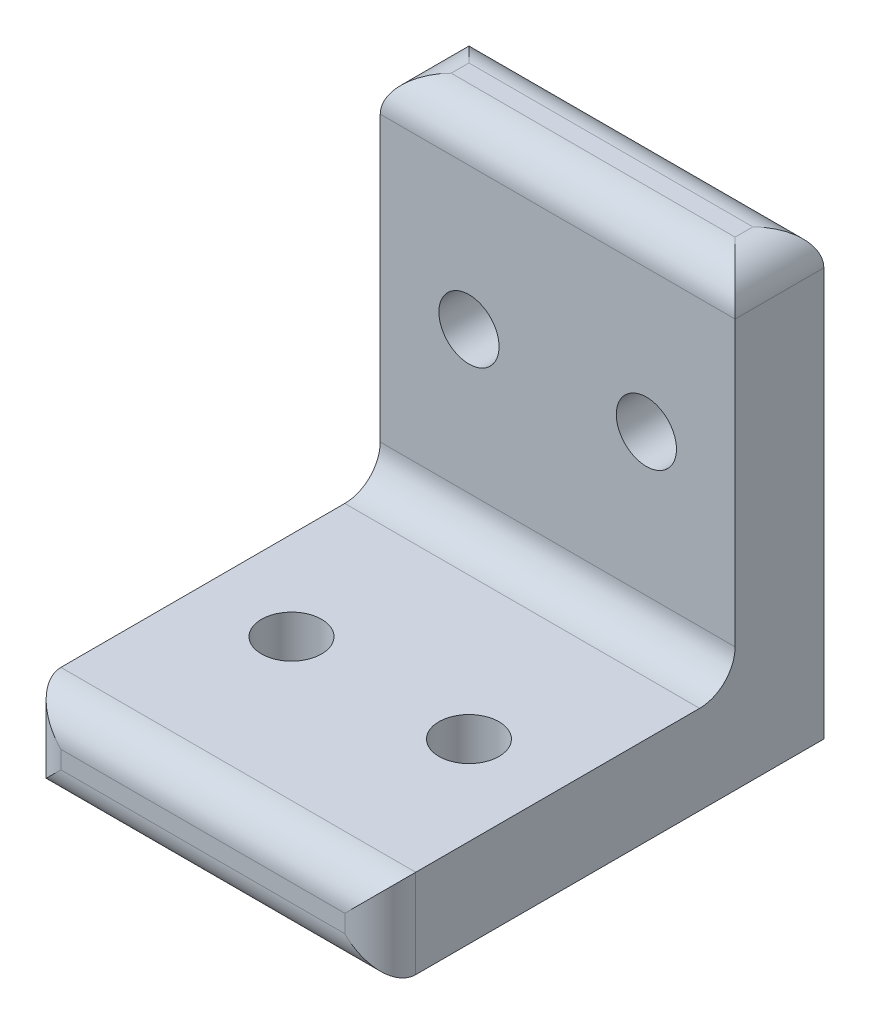
SolidWorks part; units mm, degrees
ref_plane "Front Plane" through (0, 0, 0) normal (0, 0, 1) x (1, 0, 0)
ref_plane "Top Plane" through (0, 0, 0) normal (0, 1, 0) x (1, 0, 0)
ref_plane "Right Plane" through (0, 0, 0) normal (1, 0, 0) x (0, 0, -1)
sketch "Sketch1" plane through (0, 0, 0) normal (0, 1, 0) x (1, 0, 0)
  line L1 (-12.7, -12.7) -> (12.7, -12.7)
  line L2 (-12.7, -12.7) -> (-12.7, 12.7)
  line L3 (-12.7, 12.7) -> (12.7, 12.7)
  line L4 (12.7, -12.7) -> (12.7, 12.7)
  line L5 (-12.7, -12.7) -> (12.7, 12.7) construction
  line L6 (-12.7, 12.7) -> (12.7, -12.7) construction
  point P0 (0, 0)
  dimension "D1" = 25.4
  dimension "D2" = 25.4
extrude "Boss-Extrude1" add sketch "Sketch1" along normal blind 6.35
sketch "Sketch2" plane through (0, 0, -12.7) normal (0, 0, -1) x (-1, 0, 0)
  line L1 (-12.7, 31.75) -> (12.7, 31.75)
  line L2 (-12.7, 31.75) -> (-12.7, 0)
  line L3 (-12.7, 0) -> (12.7, 0)
  line L4 (12.7, 31.75) -> (12.7, 0)
  line L5 (-12.7, 31.75) -> (12.7, 0) construction
  line L6 (-12.7, 0) -> (12.7, 31.75) construction
  point P0 (0, 15.875)
  dimension "D1" = 31.75
  dimension "D2" = 25.4
extrude "Boss-Extrude2" add sketch "Sketch2" along normal blind 6.35
fillet "Fillet1" radius 2.54 9 edges at (-12.7, 31.75, -15.875) (12.7, 31.75, -15.875) (-12.7, 3.175, 12.7) (12.7, 3.175, 12.7) (0, 31.75, -19.05) (0, 31.75, -12.7) (0, 0, 12.7) (0, 6.35, 12.7) (0, 6.35, -12.7)
sketch "Sketch3" plane through (0, 6.35, 0) normal (0, 1, 0) x (1, 0, 0)
  line L2 (-12.7, 10.16) -> (-12.7, -10.16) construction
  line L3 (12.7, -10.16) -> (12.7, 10.16) construction
  point P0 (-6.35, 0)
  point P1 (6.35, 0)
  dimension "D1" = 6.35
  dimension "D2" = 6.35
sketch "Sketch4" plane through (0, 0, -12.7) normal (0, 0, 1) x (1, 0, 0)
  line L0 (-12.7, 8.89) -> (12.7, 8.89) construction
  line L1 (-12.7, 8.89) -> (-12.7, 29.21) construction
  line L2 (12.7, 29.21) -> (12.7, 8.89) construction
  point P0 (6.35, 19.05)
  point P3 (-6.35, 19.05)
  dimension "D1" = 10.16
  dimension "D2" = 6.35
  dimension "D3" = 6.35
hole_wizard "#8 Clearance Hole1" positions "Sketch5" profile "Sketch6" hole size "#8" standard "ANSI Inch" end condition through all
sketch "Sketch5" plane through (0, 6.35, 0) normal (0, 1, 0) x (1, 0, 0)
  point P3 (-6.35, 0)
  point P6 (6.35, 0)
sketch "Sketch6" plane through (-6.35, 6.35, 0) normal (1, 0, 0) x (0, 0, 1)
  line L0 (0, 0) -> (0, 6.35)
  line L1 (0, 6.35) -> (2.1526, 6.35)
  line L2 (2.1526, 6.35) -> (2.1526, 0)
  line L5 (2.1526, 0) -> (0, 0)
  line L11 (0, -6.35) -> (0, 107.95) construction
  dimension "Thru Hole Dia." = 4.3053
  dimension "Thru Hole Depth" = 6.35
hole_wizard "#8 Clearance Hole2" positions "Sketch7" profile "Sketch8" hole size "#8" standard "ANSI Inch" end condition through all
sketch "Sketch7" plane through (0, 0, -12.7) normal (0, 0, 1) x (1, 0, 0)
  point P0 (6.35, 19.05)
  point P3 (-6.35, 19.05)
sketch "Sketch8" plane through (6.35, 19.05, -12.7) normal (1, 0, 0) x (0, -1, 0)
  line L0 (0, 0) -> (0, 6.35)
  line L1 (0, 6.35) -> (2.1526, 6.35)
  line L2 (2.1526, 6.35) -> (2.1526, 0)
  line L5 (2.1526, 0) -> (0, 0)
  line L11 (0, -6.35) -> (0, 107.95) construction
  dimension "Thru Hole Dia." = 4.3053
  dimension "Thru Hole Depth" = 6.35
